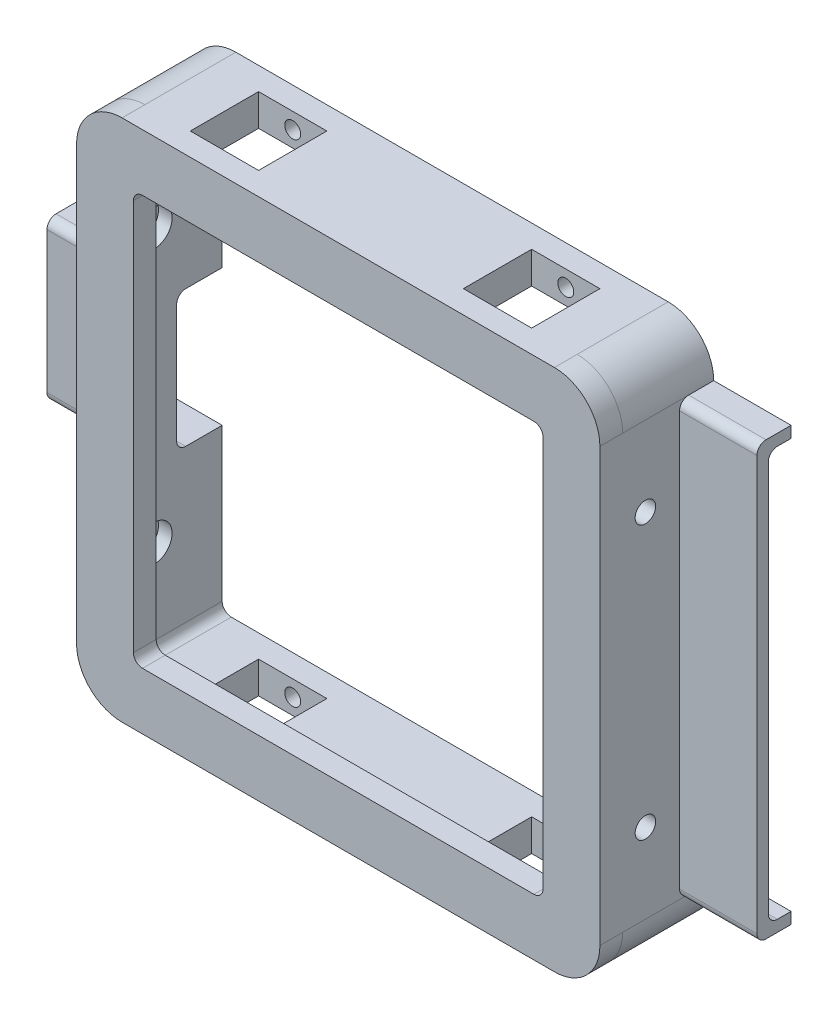
SolidWorks part; units mm, degrees
ref_plane "Front Plane" through (0, 0, 0) normal (0, 0, 1) x (1, 0, 0)
ref_plane "Top Plane" through (0, 0, 0) normal (0, 1, 0) x (1, 0, 0)
ref_plane "Right Plane" through (0, 0, 0) normal (1, 0, 0) x (0, 0, -1)
sketch "Sketch1" plane through (0, 0, 0) normal (0, 0, 1) x (1, 0, 0)
  line L1 (57.5, -57.5) -> (-57.5, -57.5)
  line L2 (57.5, -57.5) -> (57.5, 57.5)
  line L3 (57.5, 57.5) -> (-57.5, 57.5)
  line L4 (-57.5, -57.5) -> (-57.5, 57.5)
  line L5 (57.5, -57.5) -> (-57.5, 57.5) construction
  line L6 (57.5, 57.5) -> (-57.5, -57.5) construction
  point P0 (0, 0)
  dimension "D1" = 115
  dimension "D2" = 115
extrude "Boss-Extrude1" add sketch "Sketch1" along normal blind 20
fillet "Fillet1" radius 10 4 edges at (-57.5, -57.5, 10) (57.5, -57.5, 10) (-57.5, 57.5, 10) (57.5, 57.5, 10)
ref_plane "Plane1" through (0, 0, 20) normal (0, 0, 1) x (1, 0, 0)
sketch "Sketch2" plane through (0, 0, 20) normal (0, 0, 1) x (1, 0, 0)
  line L1 (50.5, -50.5) -> (-50.5, -50.5)
  line L2 (50.5, -50.5) -> (50.5, 50.5)
  line L3 (50.5, 50.5) -> (-50.5, 50.5)
  line L4 (-50.5, -50.5) -> (-50.5, 50.5)
  line L5 (50.5, -50.5) -> (-50.5, 50.5) construction
  line L6 (50.5, 50.5) -> (-50.5, -50.5) construction
  point P0 (0, 0)
  dimension "D1" = 101
  dimension "D2" = 101
extrude "Cut-Extrude1" cut sketch "Sketch2" against normal blind 30
fillet "Fillet2" radius 2 4 edges at (50.5, -50.5, 10) (-50.5, -50.5, 10) (50.5, 50.5, 10) (-50.5, 50.5, 10)
ref_plane "Plane2" through (57.5, 0, 0) normal (1, 0, 0) x (0, 0, -1)
sketch "Sketch3" plane through (57.5, 0, 0) normal (1, 0, 0) x (0, 0, -1)
  line L1 (5, -45) -> (-5, -45)
  line L2 (5, -45) -> (5, 45)
  line L3 (5, 45) -> (-5, 45)
  line L4 (-5, -45) -> (-5, 45)
  line L5 (5, -45) -> (-5, 45) construction
  line L6 (5, 45) -> (-5, -45) construction
  point P0 (0, 0)
  dimension "D1" = 10
  dimension "D2" = 90
extrude "Cut-Extrude2" cut sketch "Sketch3" against normal blind 30
sketch "Sketch4" plane through (57.5, 0, 0) normal (1, 0, 0) x (0, 0, -1)
  line L0 (-20, -47.5) -> (0, -47.5) construction
  line L1 (-5, 45) -> (0, 45)
  line L2 (-5, 45) -> (-5, 47.5)
  line L3 (-5, 47.5) -> (0, 47.5)
  line L4 (0, 45) -> (0, 47.5)
  line L5 (-5, -45) -> (0, -45)
  line L6 (-5, -45) -> (-5, -47.5)
  line L7 (-5, -47.5) -> (0, -47.5)
  line L8 (0, -45) -> (0, -47.5)
  line L9 (-5, 47.5) -> (-7.5, 47.5)
  line L10 (-5, 47.5) -> (-5, -47.5)
  line L11 (-5, -47.5) -> (-7.5, -47.5)
  line L12 (-7.5, 47.5) -> (-7.5, -47.5)
  dimension "D1" = 2.5
extrude "Boss-Extrude2" add sketch "Sketch4" along normal blind 17 contours L9 L12 L11 L6 L10 L2 | L1 L4 L3 L2 | L8 L5 L6 L7
fillet "Fillet3" radius 2 4 edges at (62.5, -45, 5) (66, -47.5, 7.5) (62.5, 45, 5) (66, 47.5, 7.5)
ref_plane "Plane3" through (-57.5, 0, 0) normal (-1, 0, 0) x (0, 0, 1)
sketch "Sketch5" plane through (-57.5, 0, 0) normal (-1, 0, 0) x (0, 0, 1)
  line L1 (10, -15) -> (-10, -15)
  line L2 (10, -15) -> (10, 15)
  line L3 (10, 15) -> (-10, 15)
  line L4 (-10, -15) -> (-10, 15)
  line L5 (10, -15) -> (-10, 15) construction
  line L6 (10, 15) -> (-10, -15) construction
  point P0 (0, 0)
  dimension "D1" = 30
  dimension "D2" = 20
extrude "Cut-Extrude3" cut sketch "Sketch5" against normal blind 22
sketch "Sketch6" plane through (-57.5, 0, 0) normal (-1, 0, 0) x (0, 0, 1)
  line L0 (0, 47.5) -> (0, 15) construction
  line L1 (10, 15) -> (0, 15)
  line L2 (10, 15) -> (10, 17.5)
  line L3 (10, 17.5) -> (0, 17.5)
  line L4 (0, 15) -> (0, 17.5)
  line L5 (0, -15) -> (0, -47.5) construction
  line L6 (10, -15) -> (0, -15)
  line L7 (10, -15) -> (10, -17.5)
  line L8 (10, -17.5) -> (0, -17.5)
  line L9 (0, -15) -> (0, -17.5)
  line L11 (10, 17.5) -> (12.5, 17.5)
  line L12 (10, 17.5) -> (10, -17.5)
  line L13 (10, -17.5) -> (12.5, -17.5)
  line L14 (12.5, 17.5) -> (12.5, -17.5)
  dimension "D1" = 2.5
  dimension "D2" = 2.5
  dimension "D3" = 2.5
extrude "Boss-Extrude3" add sketch "Sketch6" along normal blind 19 contours L14 L11 L2 L12 L7 L13 | L4 L1 L2 L3 | L6 L9 L8 L7
fillet "Fillet4" radius 2 4 edges at (-63.5, -15, 10) (-67, -17.5, 12.5) (-63.5, 15, 10) (-67, 17.5, 12.5)
ref_plane "Plane4" through (0, 57.5, 0) normal (0, 1, 0) x (1, 0, 0)
sketch "Sketch7" plane through (0, 57.5, 0) normal (0, 1, 0) x (1, 0, 0)
  line L5 (-37.5, -5) -> (-22.5, -5)
  line L6 (-37.5, -5) -> (-37.5, -25)
  line L7 (-37.5, -25) -> (-22.5, -25)
  line L8 (-22.5, -5) -> (-22.5, -25)
  line L9 (-37.5, -5) -> (-22.5, -25) construction
  line L10 (-37.5, -25) -> (-22.5, -5) construction
  line L11 (37.5, -25) -> (22.5, -25)
  line L12 (37.5, -25) -> (37.5, -5)
  line L13 (37.5, -5) -> (22.5, -5)
  line L14 (22.5, -25) -> (22.5, -5)
  line L15 (37.5, -25) -> (22.5, -5) construction
  line L16 (37.5, -5) -> (22.5, -25) construction
  point P0 (-30, -15)
  point P5 (30, -15)
  dimension "D1" = 20
  dimension "D2" = 15
  dimension "D3" = 15
  dimension "D4" = 15
  dimension "D5" = 30
  dimension "D6" = 30
  dimension "D7" = 15
  dimension "D8" = 20
extrude "Cut-Extrude4" cut sketch "Sketch7" against normal blind 120
ref_plane "Plane5" through (0, 0, 0) normal (0, 0, -1) x (-1, 0, 0)
sketch "Sketch9" plane through (0, 0, 0) normal (0, 0, -1) x (-1, 0, 0)
  circle A0 centre (-30, 54) radius 1.75
  dimension "D1" = 3.5
  dimension "D2" = 30
  dimension "D3" = 54
extrude "Cut-Extrude6" cut sketch "Sketch9" against normal blind 10
mirror "Mirror2" about plane through (0, 0, 0) normal (1, 0, 0) of "Cut-Extrude6" second plane through (0, 0, 0) second plane normal (0, 1, 0)
sketch "Sketch11" plane through (-57.5, 0, 0) normal (-1, 0, 0) x (0, 0, 1)
  circle A0 centre (15, 30) radius 2.25
  dimension "D1" = 4.5
  dimension "D2" = 15
  dimension "D3" = 30
extrude "Cut-Extrude7" cut sketch "Sketch11" against normal blind 125
mirror "Mirror3" about plane through (0, 0, 0) normal (0, 1, 0) of "Cut-Extrude7"
ref_plane "Plane6" through (-50.5, 0, 0) normal (1, 0, 0) x (0, 0, -1)
sketch "Sketch12" plane through (-50.5, 0, 0) normal (1, 0, 0) x (0, 0, -1)
  circle A0 centre (-15, 30) radius 4
  dimension "D1" = 8
extrude "Cut-Extrude8" cut sketch "Sketch12" against normal blind 3
mirror "Mirror4" about plane through (0, 0, 0) normal (1, 0, 0) of "Cut-Extrude8" second plane through (0, 0, 0) second plane normal (0, 1, 0)
sketch "Sketch14" plane through (0, 0, 20) normal (0, 0, 1) x (1, 0, 0)
  line L1 (57.5, -57.5) -> (-57.5, -57.5)
  line L2 (57.5, -57.5) -> (57.5, 57.5)
  line L3 (57.5, 57.5) -> (-57.5, 57.5)
  line L4 (-57.5, -57.5) -> (-57.5, 57.5)
  line L5 (57.5, -57.5) -> (-57.5, 57.5) construction
  line L6 (57.5, 57.5) -> (-57.5, -57.5) construction
  line L7 (45, -45) -> (-45, -45)
  line L8 (45, -45) -> (45, 45)
  line L9 (45, 45) -> (-45, 45)
  line L10 (-45, -45) -> (-45, 45)
  line L11 (45, -45) -> (-45, 45) construction
  line L12 (45, 45) -> (-45, -45) construction
  point P0 (0, 0)
  point P6 (0, 0)
  dimension "D1" = 115
  dimension "D2" = 115
  dimension "D3" = 90
  dimension "D4" = 90
extrude "Boss-Extrude4" add sketch "Sketch14" along normal blind 5
fillet "Fillet5" radius 10 4 edges at (-57.5, -57.5, 22.5) (57.5, -57.5, 22.5) (-57.5, 57.5, 22.5) (57.5, 57.5, 22.5)
ref_plane "Plane7" through (0, 0, 25) normal (0, 0, 1) x (1, 0, 0)
fillet "Fillet6" radius 2 4 edges at (-45, -45, 22.5) (45, -45, 22.5) (45, 45, 22.5) (-45, 45, 22.5)
